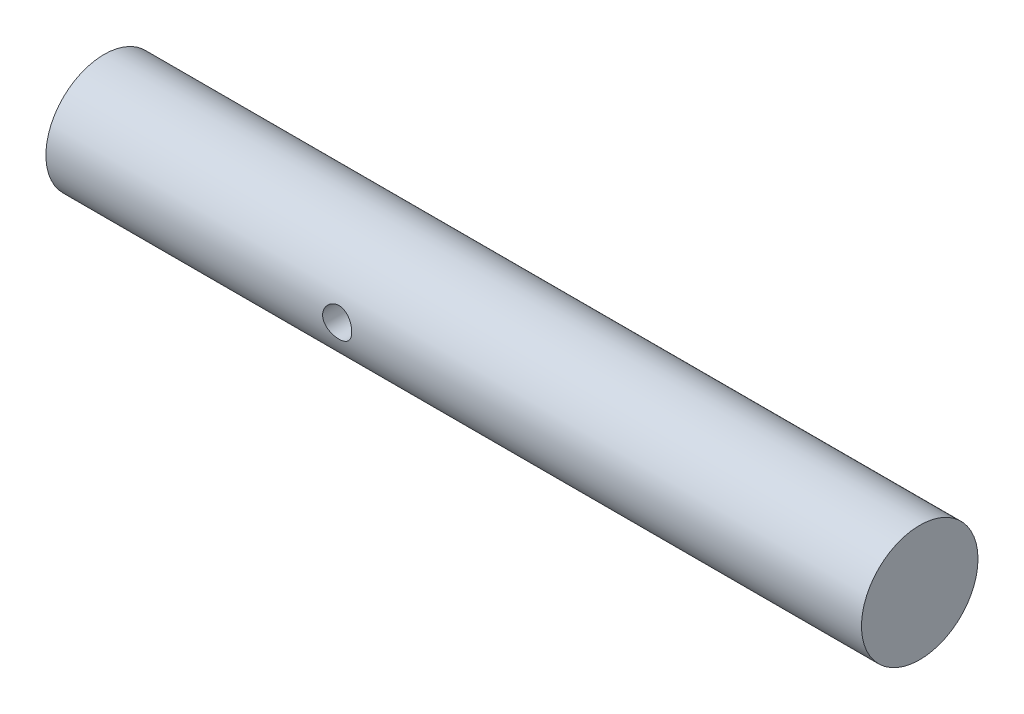
SolidWorks part; units mm, degrees
ref_plane "Front Plane" through (0, 0, 0) normal (0, 0, 1) x (1, 0, 0)
ref_plane "Top Plane" through (0, 0, 0) normal (0, 1, 0) x (1, 0, 0)
ref_plane "Right Plane" through (0, 0, 0) normal (1, 0, 0) x (0, 0, -1)
sketch "Sketch1" plane through (0, 0, 0) normal (0, 0, 1) x (1, 0, 0)
  line L0 (0, 0) -> (177.8, 0)
  point P3 (139.7, 0)
  dimension "D1" = 177.8
  dimension "D2" = 38.1
sweep "Sweep1" add path "Sketch1" circular profile diameter 25.4 parameters "D3"=25.4
sketch "Sketch18" plane through (0, 0, 0) normal (0, 0, 1) x (1, 0, 0)
  circle A0 centre (139.7, 0) radius 3.175
  dimension "D1" = 6.35
extrude "Cut-Extrude1" cut sketch "Sketch18" against normal through all contours A0
pattern_linear "LPattern1" count 4 spacing 25.4 along (-1, 0, 0) of "Cut-Extrude1"
sketch "Sketch19" plane through (0, 0, 0) normal (0, 0, -1) x (-1, 0, 0)
  circle A1 centre (-63.5, 0) radius 3.175
  circle A2 centre (-63.5, 0) radius 3.175
  dimension "D1" = 0
extrude "Cut-Extrude2" cut sketch "Sketch19" against normal through all
equation "\"bar_dia\"= 1in"
equation "\"hole_dia\"= 0.25in"
equation "\"D3@Sweep1\"=\"bar_dia\""
equation "\"D1@Sketch18\"=\"hole_dia\""
